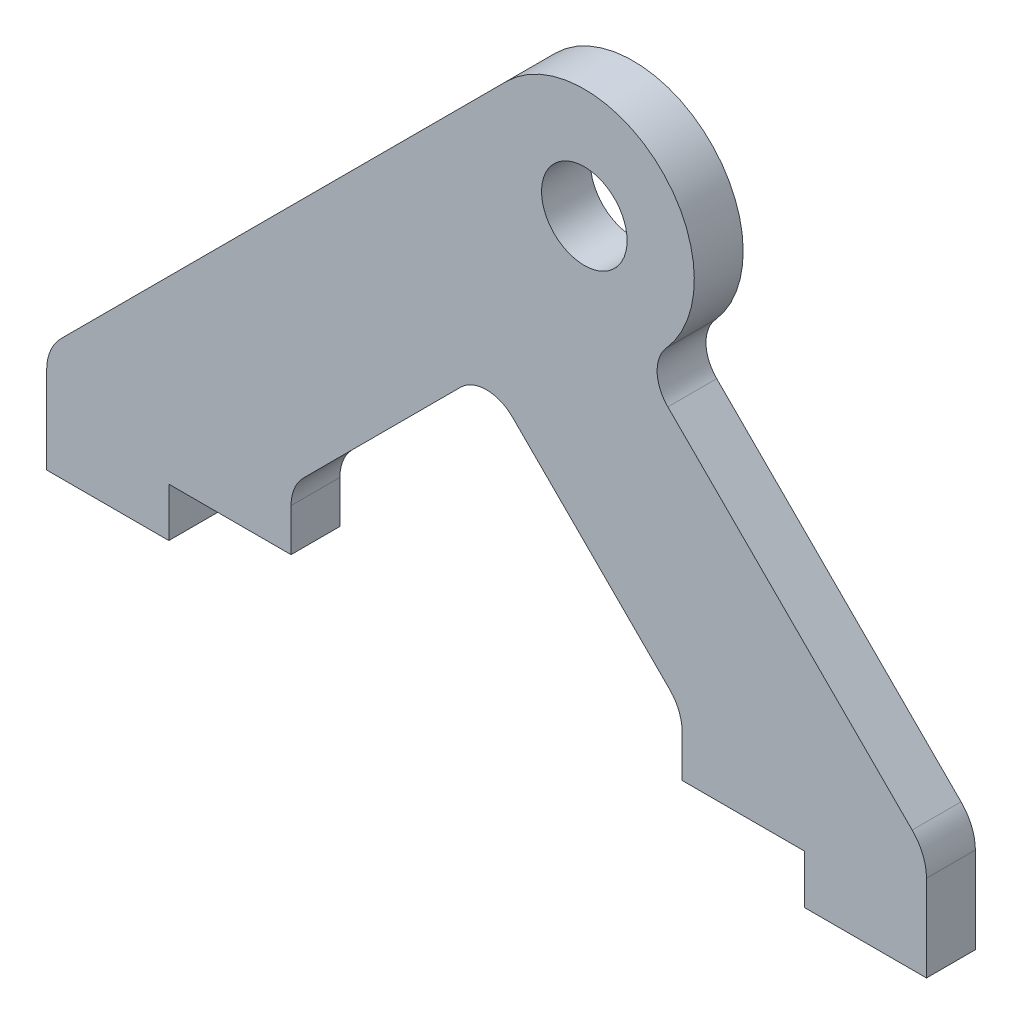
SolidWorks part; units mm, degrees
ref_plane "Front Plane" through (0, 0, 0) normal (0, 0, 1) x (1, 0, 0)
ref_plane "Top Plane" through (0, 0, 0) normal (0, 1, 0) x (1, 0, 0)
ref_plane "Right Plane" through (0, 0, 0) normal (1, 0, 0) x (0, 0, -1)
sketch "Sketch1" plane through (0, 0, 0) normal (0, 0, 1) x (1, 0, 0)
  line L0 (0, 0) -> (0, 3.5355)
  line L1 (0.5858, 4.9497) -> (18.818, 23.182)
  line L2 (0, 0) -> (5, 0)
  line L3 (5, 0) -> (5, 2)
  line L4 (5, 2) -> (10, 2)
  line L5 (10, 2) -> (10, 3.7396)
  line L6 (10.5126, 4.977) -> (16.9393, 11.4038)
  line L7 (19.0607, 11.4038) -> (25.4874, 4.977)
  line L8 (0, 4.364) -> (6.3118, 4.364) construction
  line L22 (26, 3.7396) -> (26, 2)
  line L23 (26, 2) -> (31, 2)
  line L24 (31, 2) -> (31, 0)
  line L25 (31, 0) -> (36, 0)
  line L26 (36, 0) -> (36, 3.5355)
  line L27 (35.4142, 4.9497) -> (25.4177, 14.9463)
  line L28 (10, 4.4645) -> (26, 4.4645) construction
  arc A0 (25.4177, 14.9463) -> (25.3588, 17.0052) centre (26.4783, 16.0069) cw
  arc A1 (0, 3.5355) -> (0.5858, 4.9497) centre (2, 3.5355) cw
  arc A2 (36, 3.5355) -> (35.4142, 4.9497) centre (34, 3.5355) ccw
  arc A3 (10, 3.7396) -> (10.5126, 4.977) centre (11.75, 3.7396) cw
  arc A4 (25.4874, 4.977) -> (26, 3.7396) centre (24.25, 3.7396) cw
  arc A5 (16.9393, 11.4038) -> (19.0607, 11.4038) centre (18, 10.3431) cw
  circle A8 centre (22, 20) radius 1.75
  arc A9 (25.3588, 17.0052) -> (18.818, 23.182) centre (22, 20) ccw
  dimension "D5" = 1.5
  dimension "D6" = 2
  dimension "D8" = 9
  dimension "D9" = 3.5
  dimension "D7" = 1.75
  dimension "D14" = 1.5
  dimension "D3" = 45
  dimension "D4" = 26
  dimension "D10" = 5
  dimension "D11" = 5
  dimension "D12" = 5
  dimension "D13" = 5
  dimension "D16" = 7
  dimension "D17" = 7
  dimension "D18" = 2
  dimension "D20" = 17
  dimension "D21" = 18
extrude "Boss-Extrude1" add sketch "Sketch1" along normal blind 2
